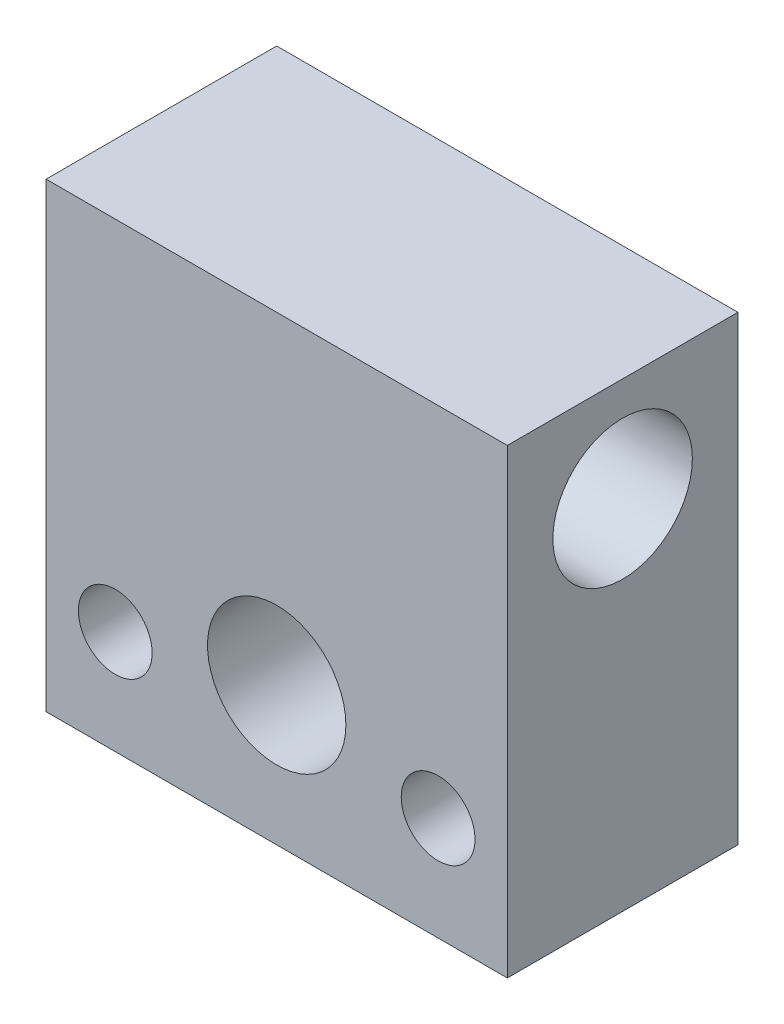
SolidWorks part; units mm, degrees
material "1.2367 (X38CrMoV5-3)"
ref_plane "Alzado" through (0, 0, 0) normal (0, 0, 1) x (1, 0, 0)
ref_plane "Planta" through (0, 0, 0) normal (0, 1, 0) x (1, 0, 0)
ref_plane "Vista lateral" through (0, 0, 0) normal (1, 0, 0) x (0, 0, -1)
ref_plane "Plano1" through (0, 0, 0) normal (0, 0, -1) x (-1, 0, 0)
sketch "Croquis1" plane through (0, 0, 0) normal (0, 0, -1) x (-1, 0, 0)
  line L0 (-10, -10) -> (10, -10)
  line L1 (10, -10) -> (10, 10)
  line L2 (10, 10) -> (-10, 10)
  line L3 (-10, 10) -> (-10, -10)
extrude "Saliente-Extruir1" add sketch "Croquis1" against normal blind 10
hole_wizard "Diámetro de taladro Ø6.0 (6)1" positions "Croquis3" profile "Croquis2" hole size "Ø6.0" standard "Ansi Metric"
sketch "Croquis3" plane through (0, 0, 10) normal (0, 0, 1) x (1, 0, 0)
  point P0 (0, -4)
sketch "Croquis2" plane through (0, -4, 10) normal (1, 0, 0) x (0, -1, 0)
  line L0 (0, 0) -> (0, 10)
  line L1 (0, 10) -> (3, 10)
  line L2 (3, 10) -> (3, 0)
  line L5 (3, 0) -> (0, 0)
  line L11 (0, -6.35) -> (0, 107.95) construction
  dimension "Diámetro de taladro hasta el siguiente" = 6
  dimension "Profundidad de taladro hasta el siguiente" = 10
hole_wizard "Diámetro de taladro Ø3.2 (3.2)1" positions "Croquis5" profile "Croquis4" hole size "Ø3.2" standard "Ansi Metric"
sketch "Croquis5" plane through (0, 0, 0) normal (0, 0, -1) x (-1, 0, 0)
  point P0 (7, -5.5)
  point P1 (-7, -5.5)
sketch "Croquis4" plane through (-7, -5.5, 0) normal (1, 0, 0) x (0, 1, 0)
  line L0 (0, 0) -> (0, 10)
  line L1 (0, 10) -> (1.6, 10)
  line L2 (1.6, 10) -> (1.6, 0)
  line L5 (1.6, 0) -> (0, 0)
  line L11 (0, -6.35) -> (0, 107.95) construction
  dimension "Diámetro de taladro hasta el siguiente" = 3.2
  dimension "Profundidad de taladro hasta el siguiente" = 10
hole_wizard "Diámetro de taladro Ø3.0 (3)1" positions "Croquis7" profile "Croquis6" hole size "Ø3.0" standard "Ansi Metric"
sketch "Croquis7" plane through (-10, 0, 0) normal (-1, 0, 0) x (0, 0, 1)
  point P0 (5.5, -1.5)
sketch "Croquis6" plane through (-10, -1.5, 5.5) normal (0, 1, 0) x (0, 0, 1)
  line L0 (0, 0) -> (0, 4)
  line L1 (0, 4) -> (1.5, 4)
  line L2 (1.5, 4) -> (1.5, 0)
  line L5 (1.5, 0) -> (0, 0)
  line L10 (0, 4) -> (-1.5, 4) construction
  line L11 (0, -6.35) -> (0, 107.95) construction
  dimension "Diámetro de taladro" = 3
  dimension "Profundidad de taladro" = 4
  dimension "Ángulo de perforador" = 180
hole_wizard "Diámetro de taladro Ø2.0 (2)1" positions "Croquis9" profile "Croquis8" hole size "Ø2.0" standard "Ansi Metric"
sketch "Croquis9" plane through (-10, 0, 0) normal (-1, 0, 0) x (0, 0, 1)
  point P0 (2, -1.5)
sketch "Croquis8" plane through (-10, -1.5, 2) normal (0, 1, 0) x (0, 0, 1)
  line L0 (0, 0) -> (0, 5)
  line L1 (0, 5) -> (1, 5)
  line L2 (1, 5) -> (1, 0)
  line L5 (1, 0) -> (0, 0)
  line L10 (0, 5) -> (-1, 5) construction
  line L11 (0, -6.35) -> (0, 107.95) construction
  dimension "Diámetro de taladro" = 2
  dimension "Profundidad de taladro" = 5
  dimension "Ángulo de perforador" = 180
hole_wizard "Taladro1" positions "Croquis11" profile "Croquis10" legacy
sketch "Croquis11" plane through (10, 0, 0) normal (1, 0, 0) x (0, 0, -1)
  point P0 (-5, 5.5)
sketch "Croquis10" plane through (10, 5.5, 5) normal (0, 1, 0) x (0, 0, -1)
  line L0 (0, 0) -> (0, 20)
  line L1 (0, 20) -> (3.025, 20)
  line L2 (3.025, 20) -> (3.025, 0)
  line L3 (3.025, 0) -> (0, 0)
  line L4 (0, 110) -> (0, -10) construction
  dimension "Diámetro" = 6.05
  dimension "Profundidad" = 20
hole_wizard "Diámetro de taladro Ø3.0 (3)2" positions "Croquis13" profile "Croquis12" hole size "Ø3.0" standard "Ansi Metric"
sketch "Croquis13" plane through (0, 0, 0) normal (0, 0, -1) x (-1, 0, 0)
  point P0 (0, 5.5)
sketch "Croquis12" plane through (0, 5.5, 0) normal (1, 0, 0) x (0, 1, 0)
  line L0 (0, 0) -> (0, 1.975)
  line L1 (0, 1.975) -> (1.5, 1.975)
  line L2 (1.5, 1.975) -> (1.5, 0)
  line L5 (1.5, 0) -> (0, 0)
  line L11 (0, -6.35) -> (0, 107.95) construction
  dimension "Diámetro de taladro hasta el siguiente" = 3
  dimension "Profundidad de taladro hasta el siguiente" = 1.975
chamfer "Chaflán1" distance 1.2 angle 45 2 edges at (5.4, -5.5, 0) (-8.6, -5.5, 0)
sketch "Croquis14" plane through (0, 10, 0) normal (0, 1, 0) x (1, 0, 0)
  line L0 (-10.9386, 0) -> (11.6386, 0) construction
